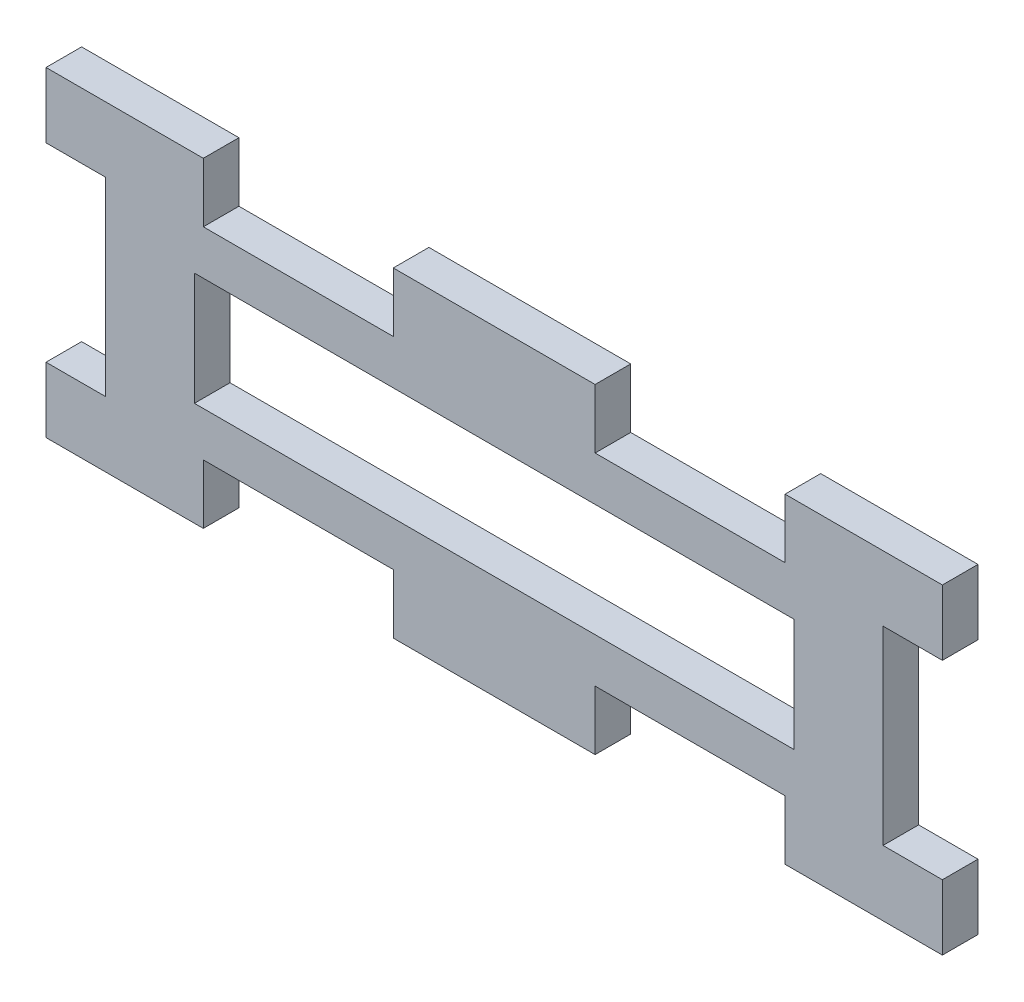
SolidWorks part; units mm, degrees
material "Hêtre"
ref_plane "Plan de face" through (0, 0, 0) normal (0, 0, 1) x (1, 0, 0)
ref_plane "Plan de dessus" through (0, 0, 0) normal (0, 1, 0) x (1, 0, 0)
ref_plane "Plan de droite" through (0, 0, 0) normal (1, 0, 0) x (0, 0, -1)
sketch "Esquisse1" plane through (0, 0, 0) normal (0, 0, 1) x (1, 0, 0)
  line L0 (59.5, 11) -> (59.5, -11) construction
  line L1 (50.5, -9.5) -> (-50.5, -9.5)
  line L2 (50.5, -9.5) -> (50.5, 9.5)
  line L3 (50.5, 9.5) -> (-50.5, 9.5)
  line L4 (-50.5, -9.5) -> (-50.5, 9.5)
  line L5 (75.5, -27) -> (-75.5, -27)
  line L6 (75.5, -27) -> (75.5, 27)
  line L7 (75.5, 27) -> (-75.5, 27)
  line L8 (-75.5, -27) -> (-75.5, 27)
  line L9 (-59.5, 11) -> (59.5, 11) construction
  line L10 (59.5, -11) -> (-59.5, -11) construction
  line L11 (-59.5, -11) -> (-59.5, 11) construction
  dimension "D1" = 16
  dimension "D2" = 16
  dimension "D3" = 16
  dimension "D4" = 16
extrude "Boss.-Extru.1" add sketch "Esquisse1" against normal blind 6
sketch "Esquisse2" plane through (0, 0, 0) normal (0, 0, 1) x (1, 0, 0)
  line L0 (-75.5, 27) -> (-75.5, -27) construction
  line L1 (-75.5, 16) -> (-65.5, 16)
  line L2 (-75.5, 16) -> (-75.5, -16)
  line L3 (-75.5, -16) -> (-65.5, -16)
  line L4 (-65.5, 16) -> (-65.5, -16)
  line L5 (0, 27) -> (0, -27) construction
  line L6 (75.5, 27) -> (-75.5, 27) construction
  line L7 (-75.5, -27) -> (75.5, -27) construction
  line L8 (65.5, 16) -> (65.5, -16)
  line L9 (75.5, -16) -> (65.5, -16)
  line L10 (75.5, 16) -> (75.5, -16)
  line L11 (75.5, 16) -> (65.5, 16)
  line L12 (-75.5, 0) -> (75.5, 0) construction
  point P6 (-75.5, 0)
  point P17 (75.5, 0)
  dimension "D1" = 32
  dimension "D2" = 10
extrude "Enlèv. mat.-Extru.1" cut sketch "Esquisse2" against normal blind 6
sketch "Esquisse4" plane through (0, 0, 0) normal (0, 0, 1) x (1, 0, 0)
  line L0 (75.5, 27) -> (-75.5, 27) construction
  line L1 (17, 27) -> (49, 27)
  line L2 (17, 27) -> (17, 17)
  line L3 (17, 17) -> (49, 17)
  line L4 (49, 27) -> (49, 17)
  line L5 (0, 0) -> (0, 49.1686) construction
  line L6 (0, 0) -> (89.7616, 0) construction
  line L7 (-49, 27) -> (-49, 17)
  line L8 (-17, 17) -> (-49, 17)
  line L9 (-17, 27) -> (-17, 17)
  line L10 (-17, 27) -> (-49, 27)
  line L11 (-17, -27) -> (-49, -27)
  line L12 (-17, -27) -> (-17, -17)
  line L13 (-17, -17) -> (-49, -17)
  line L14 (-49, -27) -> (-49, -17)
  line L15 (49, -27) -> (49, -17)
  line L16 (17, -17) -> (49, -17)
  line L17 (17, -27) -> (17, -17)
  line L18 (17, -27) -> (49, -27)
  dimension "D1" = 10
  dimension "D2" = 32
  dimension "D3" = 17
extrude "Enlèv. mat.-Extru.2" cut sketch "Esquisse4" against normal blind 10
equation "\"D1@Esquisse1\"=\"D4@Esquisse1\""
equation "\"D2@Esquisse1\"=\"D3@Esquisse1\""
